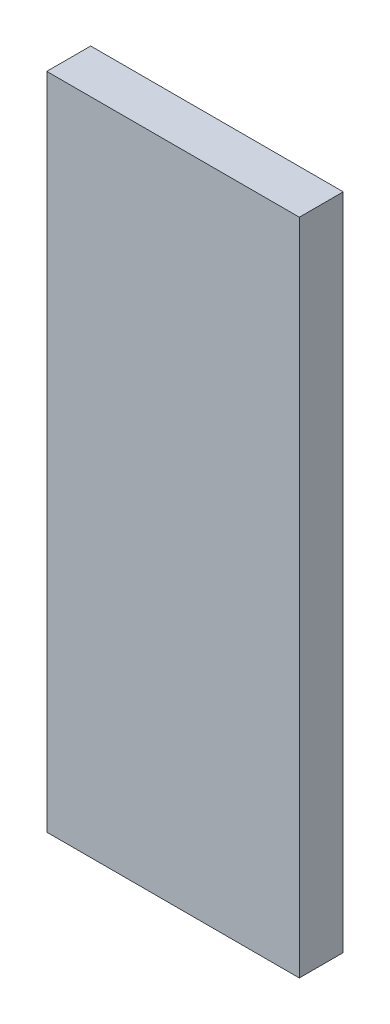
SolidWorks part; units mm, degrees
ref_plane "Front Plane" through (0, 0, 0) normal (0, 0, 1) x (1, 0, 0)
ref_plane "Top Plane" through (0, 0, 0) normal (0, 1, 0) x (1, 0, 0)
ref_plane "Right Plane" through (0, 0, 0) normal (1, 0, 0) x (0, 0, -1)
sketch "Sketch1" plane through (0, 0, 0) normal (0, 1, 0) x (1, 0, 0)
  line L1 (0, 0) -> (15, 0)
  line L2 (0, 0) -> (0, -80)
  line L3 (0, -80) -> (15, -80)
  line L4 (15, 0) -> (15, -80)
  dimension "D1" = 15
  dimension "D2" = 80
extrude "Boss-Extrude1" add sketch "Sketch1" along normal blind 5
sketch "Sketch3" plane through (0, 0, 0) normal (0, 0, -1) x (-1, 0, 0)
  line L1 (-19, 0) -> (4, 0)
  line L2 (-19, 0) -> (-19, 60)
  line L3 (-19, 60) -> (4, 60)
  line L4 (4, 0) -> (4, 60)
  dimension "D1" = 0
  dimension "D2" = 4
  dimension "D3" = 4
  dimension "D4" = 60
extrude "Boss-Extrude3" add sketch "Sketch3" along normal blind 4
sketch "Sketch5" plane through (0, 0, -4) normal (0, 0, -1) x (-1, 0, 0)
  line L0 (4, 60) -> (-19, 60) construction
  line L1 (1.75, 60) -> (-2.25, 60)
  line L2 (1.75, 60) -> (1.75, 10)
  line L3 (1.75, 10) -> (-2.25, 10)
  line L4 (-2.25, 60) -> (-2.25, 10)
  point P6 (-0.25, 60)
  point P7 (-7.5, 60)
  dimension "D1" = 7.25
  dimension "D2" = 4
  dimension "D3" = 50
extrude "Boss-Extrude5" add sketch "Sketch5" along normal blind 15
sketch "Sketch6" plane through (0, 0, 80) normal (0, 0, 1) x (1, 0, 0)
  line L1 (15, 0) -> (0, 0)
  line L2 (15, 0) -> (15, 5)
  line L3 (15, 5) -> (0, 5)
  line L4 (0, 0) -> (0, 5)
extrude "Cut-Extrude1" cut sketch "Sketch6" against normal blind 80
sketch "Sketch7" plane through (0, 0, -19) normal (0, 0, -1) x (-1, 0, 0)
  line L0 (1.75, 10) -> (1.75, 60) construction
  line L1 (-2.25, 60) -> (1.75, 60)
  line L2 (-2.25, 60) -> (-2.25, 45)
  line L3 (-2.25, 45) -> (1.75, 45)
  line L4 (1.75, 60) -> (1.75, 45)
  dimension "D1" = 15
extrude "Cut-Extrude2" cut sketch "Sketch7" against normal blind 15
